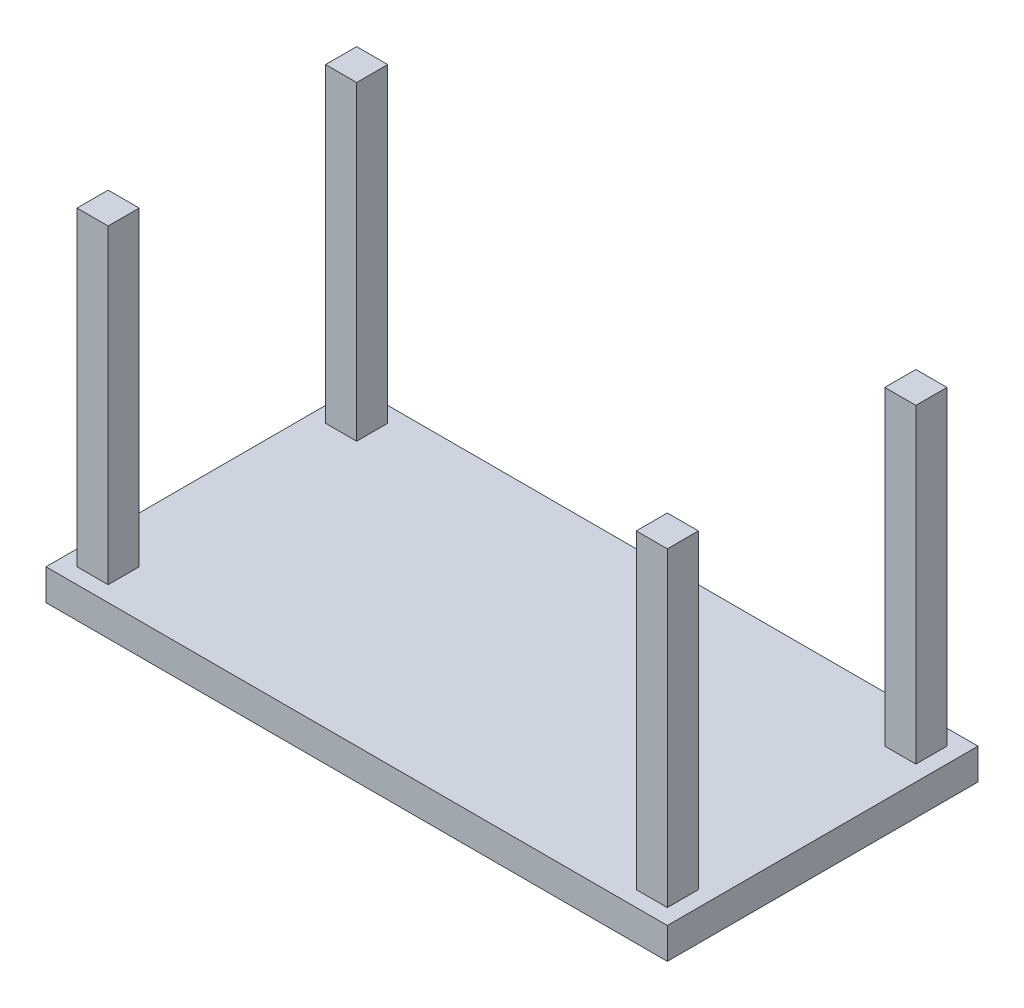
SolidWorks part; units mm, degrees
ref_plane "Front Plane" through (0, 0, 0) normal (0, 0, 1) x (1, 0, 0)
ref_plane "Top Plane" through (0, 0, 0) normal (0, 1, 0) x (1, 0, 0)
ref_plane "Right Plane" through (0, 0, 0) normal (1, 0, 0) x (0, 0, -1)
sketch "Sketch1" plane through (0, 0, 0) normal (0, 1, 0) x (1, 0, 0)
  line L1 (100, 50) -> (-100, 50)
  line L2 (100, 50) -> (100, -50)
  line L3 (100, -50) -> (-100, -50)
  line L4 (-100, 50) -> (-100, -50)
  line L5 (100, 50) -> (-100, -50) construction
  line L6 (100, -50) -> (-100, 50) construction
  point P0 (0, 0)
  dimension "D1" = 100
  dimension "D2" = 200
extrude "Boss-Extrude1" add sketch "Sketch1" along normal blind 10
sketch "Sketch2" plane through (0, 10, 0) normal (0, 1, 0) x (1, 0, 0)
  line L0 (0, 50) -> (0, -50) construction
  line L1 (-95, 45) -> (-85, 45)
  line L2 (-95, 45) -> (-95, 35)
  line L3 (-95, 35) -> (-85, 35)
  line L4 (-85, 45) -> (-85, 35)
  line L5 (-95, 45) -> (-85, 35) construction
  line L6 (-95, 35) -> (-85, 45) construction
  line L7 (100, 50) -> (-100, 50) construction
  line L8 (-100, -50) -> (100, -50) construction
  line L9 (-100, 0) -> (100, 0) construction
  line L10 (-100, 50) -> (-100, -50) construction
  line L11 (100, -50) -> (100, 50) construction
  line L12 (95, 45) -> (95, 35)
  line L13 (95, 35) -> (85, 35)
  line L14 (85, 45) -> (85, 35)
  line L15 (95, 45) -> (85, 45)
  line L16 (95, -45) -> (95, -35)
  line L17 (85, -45) -> (85, -35)
  line L18 (95, -45) -> (85, -45)
  line L19 (95, -35) -> (85, -35)
  line L20 (-95, -35) -> (-85, -35)
  line L21 (-95, -45) -> (-95, -35)
  line L22 (-85, -45) -> (-85, -35)
  line L23 (-95, -45) -> (-85, -45)
  point P0 (-90, 40)
  dimension "D1" = 10
  dimension "D2" = 10
  dimension "D3" = 40
  dimension "D4" = 90
extrude "Boss-Extrude2" add sketch "Sketch2" along normal blind 100
